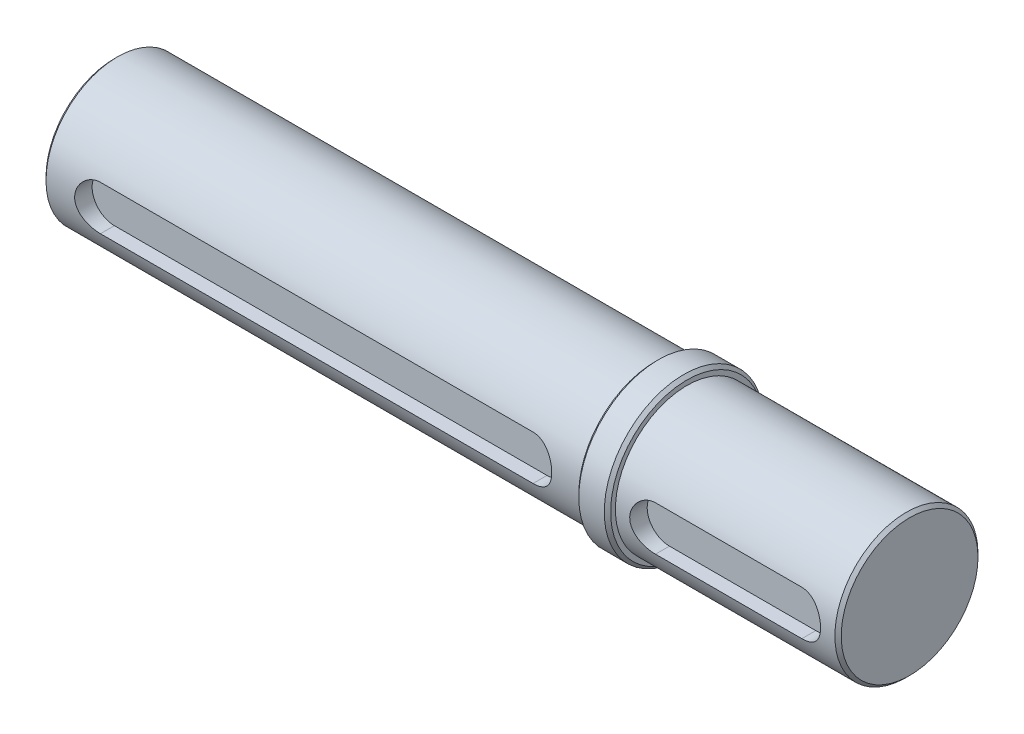
SolidWorks part; units mm, degrees
material "Сталь 20 ГОСТ 535-88"
ref_plane "Спереди" through (0, 0, 0) normal (0, 0, 1) x (1, 0, 0)
ref_plane "Сверху" through (0, 0, 0) normal (0, 1, 0) x (1, 0, 0)
ref_plane "Справа" through (0, 0, 0) normal (1, 0, 0) x (0, 0, -1)
other "Configuration Table"
sketch "Эскиз1" plane through (0, 0, 0) normal (0, 0, 1) x (1, 0, 0)
  line L0 (0, 0) -> (0, 22.5)
  line L1 (0, 22.5) -> (170, 22.5)
  line L2 (170, 22.5) -> (170, 25)
  line L3 (170, 25) -> (180, 25)
  line L4 (180, 25) -> (180, 22.5)
  line L5 (180, 22.5) -> (250, 22.5)
  line L6 (250, 22.5) -> (250, 0)
  line L7 (250, 0) -> (0, 0)
  line L8 (0, 0) -> (-23.5502, 0) construction
  dimension "D1" = 45
  dimension "D2" = 50
  dimension "D3" = 45
  dimension "D4" = 70
  dimension "D5" = 10
  dimension "D6" = 170
revolve "Повернуть1" add sketch "Эскиз1" angle 360 about L8
hole_wizard "Отверстие обработанное метчиком M101" positions "Эскиз2" profile "Эскиз3" tap size "M10" standard "DIN"
sketch "Эскиз2" plane through (0, 0, 0) normal (-1, 0, 0) x (0, 0, 1)
  point P0 (0, 0)
sketch "Эскиз3" plane through (0, 0, 0) normal (0, 1, 0) x (0, 0, 1)
  line L0 (0, 0) -> (0, 55.0537)
  line L1 (0, 55.0537) -> (4.25, 52.5)
  line L2 (4.25, 52.5) -> (4.25, 0)
  line L5 (4.25, 0) -> (0, 0)
  line L10 (0, 55.0537) -> (-4.25, 52.5) construction
  line L11 (0, -6.35) -> (0, 107.95) construction
  dimension "Диаметр сверла" = 8.5
  dimension "Глубина сверла" = 52.5
  dimension "Угол заточки сверла" = 118
cosmetic thread "Отверстие резьбы1" parameters "D1"=45, "D2"=10
chamfer "Фаска1" distance 1 angle 45 4 edges at (250, 0, -22.5) (0, 0, -22.5) (170, 0, -25) (180, 0, -25)
sketch "Эскиз4" plane through (0, 0, 0) normal (0, 0, 1) x (1, 0, 0)
  line L0 (237.5, 0) -> (191.5, 0) construction
  line L1 (237.5, -7) -> (191.5, -7)
  line L2 (237.5, 7) -> (191.5, 7)
  line L3 (250, -21.5) -> (250, 21.5) construction
  arc A0 (237.5, -7) -> (237.5, 7) centre (237.5, 0) ccw
  arc A1 (191.5, 7) -> (191.5, -7) centre (191.5, 0) ccw
  point P3 (214.5, 0)
  dimension "D1" = 14
  dimension "D2" = 12.5
  dimension "D3" = 60
extrude "Вырез-Вытянуть1" cut sketch "Эскиз4" against normal blind 5.5 from offset 22.5
sketch "Эскиз5" plane through (0, 0, 0) normal (0, 0, 1) x (1, 0, 0)
  line L0 (0, 0) -> (170, 0) construction
  line L3 (170, 22.5) -> (170, -22.5) construction
  line L4 (17, 0) -> (153, 0) construction
  line L5 (17, 7) -> (153, 7)
  line L6 (17, -7) -> (153, -7)
  arc A0 (17, 7) -> (17, -7) centre (17, 0) ccw
  arc A1 (153, -7) -> (153, 7) centre (153, 0) ccw
  point P4 (85, 0)
  dimension "D2" = 150
  dimension "D1" = 14
extrude "Вырез-Вытянуть2" cut sketch "Эскиз5" against normal blind 5.5 from offset 22.5
